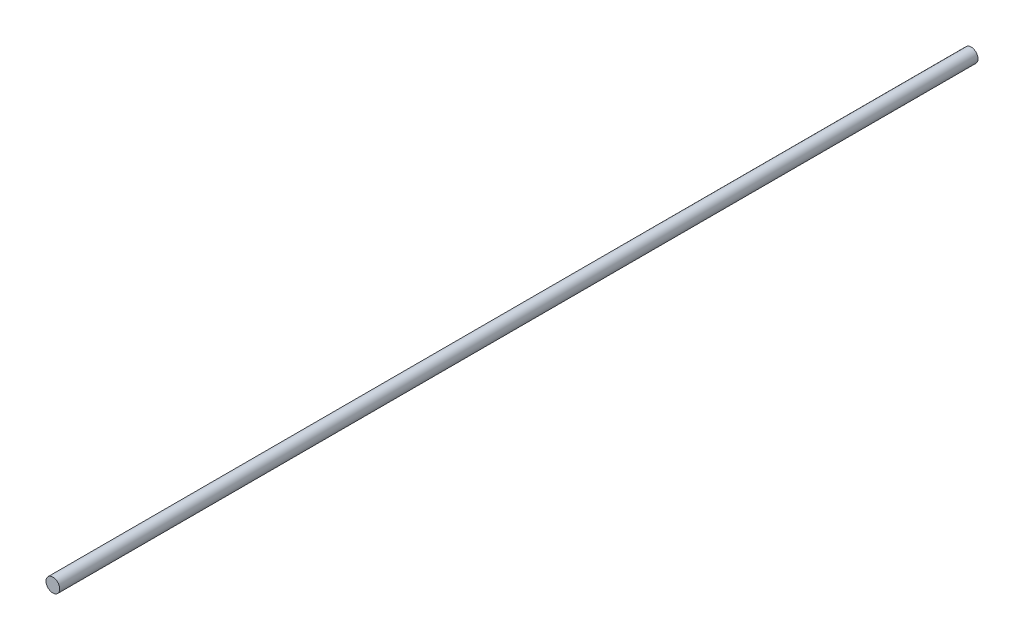
SolidWorks part; units mm, degrees
ref_plane "前视基准面" through (0, 0, 0) normal (0, 0, 1) x (1, 0, 0)
ref_plane "上视基准面" through (0, 0, 0) normal (0, 1, 0) x (1, 0, 0)
ref_plane "右视基准面" through (0, 0, 0) normal (1, 0, 0) x (0, 0, -1)
sketch "草图1" plane through (0, 0, 0) normal (0, 0, 1) x (1, 0, 0)
  circle A0 centre (0, 0) radius 7.5
  dimension "D1" = 15
extrude "凸台-拉伸1" add sketch "草图1" along normal blind 1000
